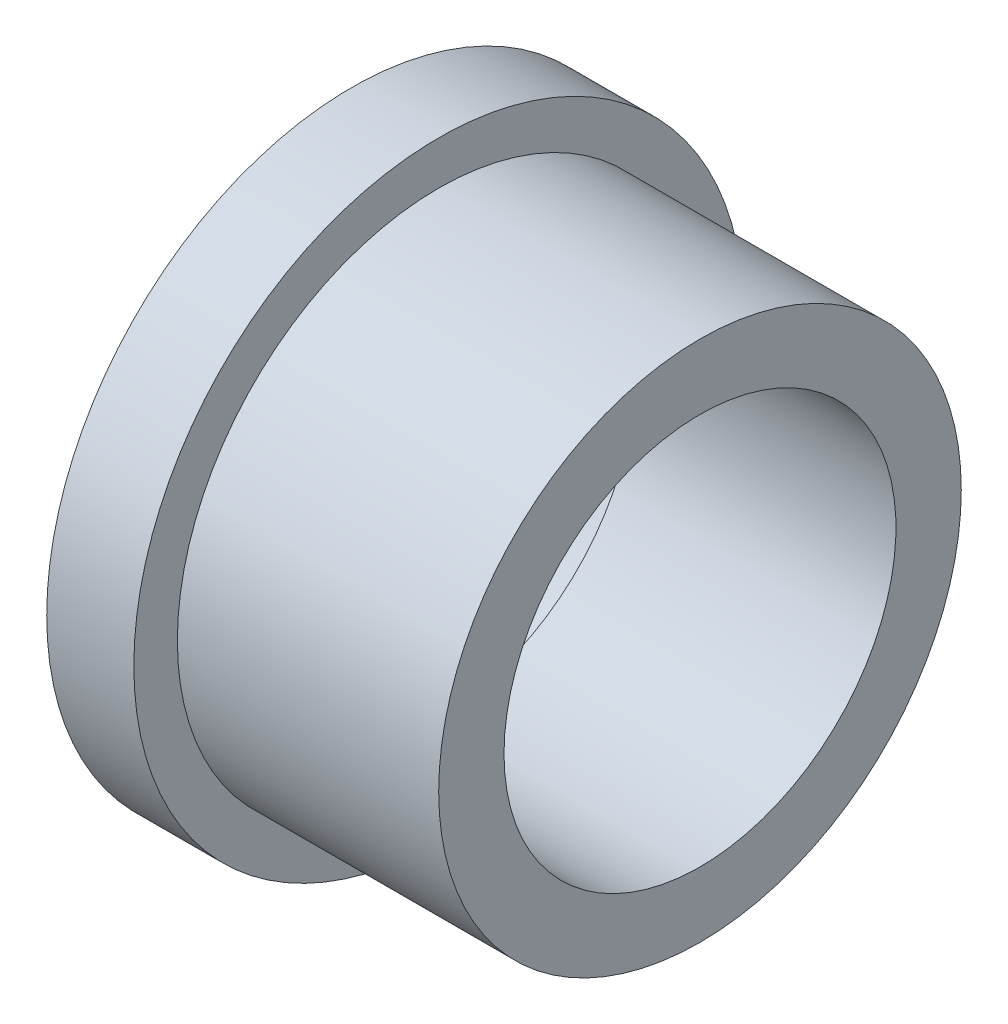
SolidWorks part; units mm, degrees
ref_plane "Front Plane" through (0, 0, 0) normal (0, 0, 1) x (1, 0, 0)
ref_plane "Top Plane" through (0, 0, 0) normal (0, 1, 0) x (1, 0, 0)
ref_plane "Right Plane" through (0, 0, 0) normal (1, 0, 0) x (0, 0, -1)
sketch "Sketch1" plane through (0, 0, 0) normal (0, 0, 1) x (1, 0, 0)
  line L0 (0, 0) -> (14.5153, 0) construction
  line L1 (0, 2.1) -> (0, 3.5)
  line L2 (0, 3.5) -> (1, 3.5)
  line L3 (1, 3.5) -> (1, 3)
  line L4 (1, 3) -> (4, 3)
  line L5 (4, 3) -> (4, 2.25)
  line L6 (4, 2.25) -> (1, 2.25)
  line L7 (1, 2.25) -> (1, 2.6)
  line L8 (1, 2.6) -> (0.5, 2.6)
  line L9 (0.5, 2.6) -> (0.5, 2.1)
  line L10 (0.5, 2.1) -> (0, 2.1)
  point P11 (0.3973, 2.0512)
  dimension "D1" = 4.5
  dimension "D2" = 6
  dimension "D3" = 1
  dimension "D4" = 7
  dimension "D5" = 3
  dimension "D6" = 4.2
  dimension "D7" = 5.2
  dimension "D8" = 0.5
  dimension "D9" = 0.5
revolve "Revolve1" add sketch "Sketch1" angle 360 about L0
cosmetic thread "Cosmetic Thread1" parameters "D2"=5
